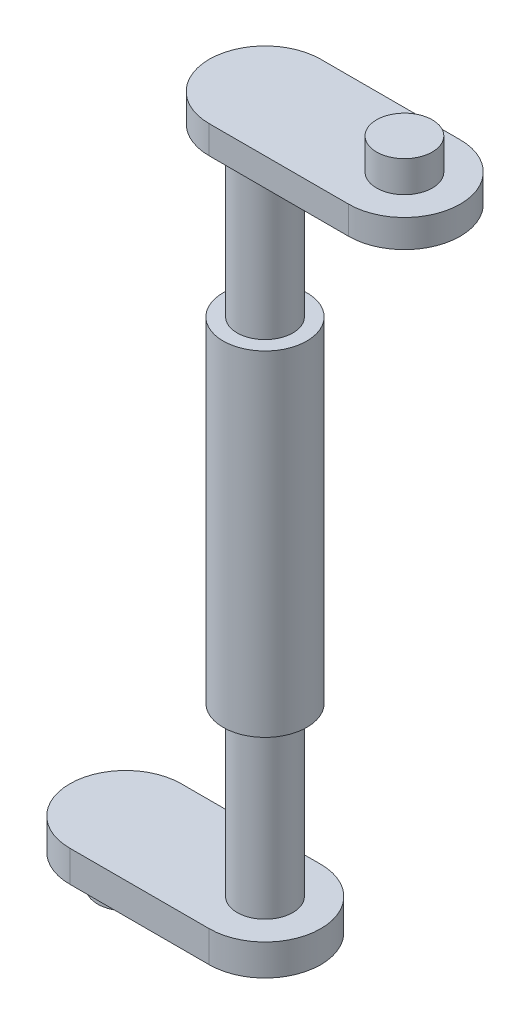
SolidWorks part; units mm, degrees
ref_plane "Front Plane" through (0, 0, 0) normal (0, 0, 1) x (1, 0, 0)
ref_plane "Top Plane" through (0, 0, 0) normal (0, 1, 0) x (1, 0, 0)
ref_plane "Right Plane" through (0, 0, 0) normal (1, 0, 0) x (0, 0, -1)
sketch "Sketch1" plane through (0, 0, 0) normal (0, 1, 0) x (1, 0, 0)
  circle A0 centre (0, 0) radius 2.5
  dimension "D1" = 5
extrude "Boss-Extrude1" add sketch "Sketch1" along normal mid plane 60 contours A0
sketch "Sketch6" plane through (0, 0, 0) normal (0, 1, 0) x (1, 0, 0)
  circle A0 centre (0, 0) radius 3.75
  dimension "D1" = 7.5
extrude "Boss-Extrude6" add sketch "Sketch6" along normal mid plane 30
sketch "Sketch2" plane through (0, 30, 0) normal (0, 1, 0) x (1, 0, 0)
  line L0 (0, 0) -> (12.5, 0) construction
  line L1 (0, 5) -> (12.5, 5)
  line L2 (0, -5) -> (12.5, -5)
  arc A0 (0, 5) -> (0, -5) centre (0, 0) ccw
  arc A1 (12.5, -5) -> (12.5, 5) centre (12.5, 0) ccw
  point P3 (6.25, 0)
  dimension "D1" = 5
  dimension "D2" = 12.5
extrude "Boss-Extrude2" add sketch "Sketch2" along normal blind 2.5
sketch "Sketch3" plane through (0, 32.5, 0) normal (0, 1, 0) x (1, 0, 0)
  circle A0 centre (12.5, 0) radius 2.5
  dimension "D2" = 5
  dimension "D1" = 12.5
extrude "Boss-Extrude3" add sketch "Sketch3" along normal blind 2.8 contours A0
sketch "Sketch4" plane through (0, -30, 0) normal (0, -1, 0) x (1, 0, 0)
  line L0 (0, 0) -> (-12.5, 0) construction
  line L1 (0, -5) -> (-12.5, -5)
  line L2 (0, 5) -> (-12.5, 5)
  arc A0 (0, -5) -> (0, 5) centre (0, 0) ccw
  arc A1 (-12.5, 5) -> (-12.5, -5) centre (-12.5, 0) ccw
  point P3 (-6.25, 0)
  dimension "D1" = 5
  dimension "D2" = 12.5
extrude "Boss-Extrude4" add sketch "Sketch4" along normal blind 2.8
sketch "Sketch5" plane through (0, -32.8, 0) normal (0, -1, 0) x (1, 0, 0)
  circle A0 centre (-12.5, 0) radius 2.5
  dimension "D1" = 5
  dimension "D2" = 12.5
extrude "Boss-Extrude5" add sketch "Sketch5" along normal blind 2.8 contours A0
